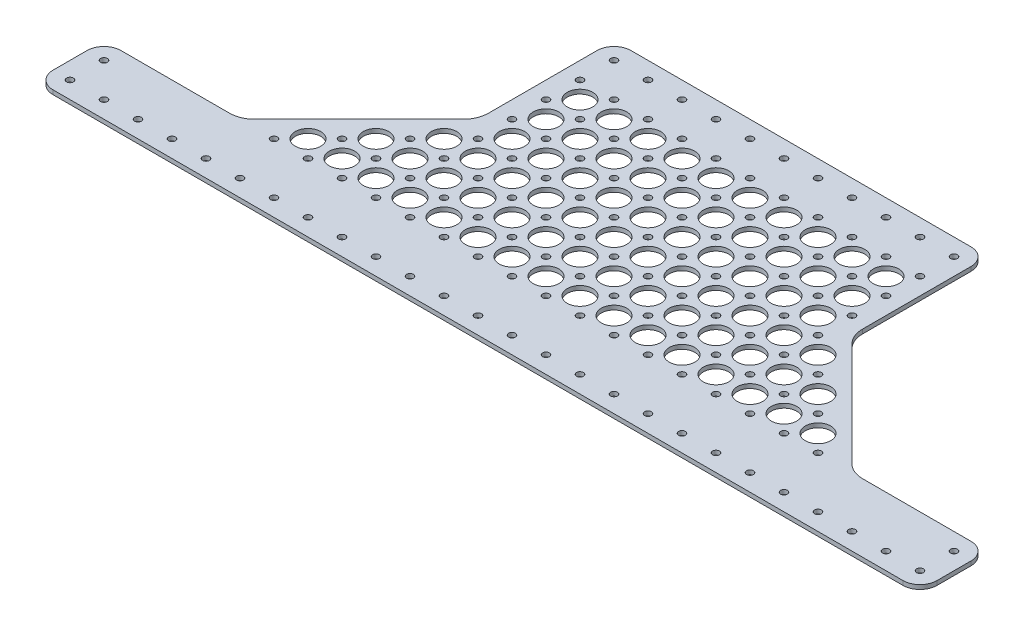
SolidWorks part; units mm, degrees
material "6061 Alloy"
ref_plane "Front Plane" through (0, 0, 0) normal (0, 0, 1) x (1, 0, 0)
ref_plane "Top Plane" through (0, 0, 0) normal (0, 1, 0) x (1, 0, 0)
ref_plane "Right Plane" through (0, 0, 0) normal (1, 0, 0) x (0, 0, -1)
sketch "Sketch1" plane through (0, 0, 0) normal (0, 1, 0) x (1, 0, 0)
  line L0 (0, 0) -> (0, 101.6)
  line L1 (0, 101.6) -> (279.4, 101.6)
  line L2 (279.4, 101.6) -> (279.4, 0)
  line L3 (279.4, 0) -> (368.3045, -88.9045)
  line L4 (368.3045, -88.9045) -> (469.9045, -88.9045)
  line L5 (469.9045, -88.9045) -> (469.9045, -419.1045)
  line L6 (469.9045, -419.1045) -> (368.3045, -419.1045)
  line L7 (368.3045, -419.1045) -> (279.4, -508.0091)
  line L8 (279.4, -508.0091) -> (279.4, -609.6091)
  line L9 (279.4, -609.6091) -> (0, -609.6091)
  line L10 (0, -609.6091) -> (0, -508.0091)
  line L11 (0, -508.0091) -> (-88.9045, -419.1045)
  line L12 (-88.9045, -419.1045) -> (-190.5045, -419.1045)
  line L13 (-190.5045, -419.1045) -> (-190.5045, -88.9045)
  line L14 (-190.5045, -88.9045) -> (-88.9045, -88.9045)
  line L15 (-88.9045, -88.9045) -> (0, 0)
  line L16 (-190.5045, -88.9045) -> (-177.8045, -88.9045)
  line L17 (-177.8045, -88.9045) -> (-177.8045, -419.1045) construction
  line L18 (-177.8045, -419.1045) -> (-190.5045, -419.1045)
  line L19 (-177.8045, -101.6045) -> (-177.8045, -127.0045) construction
  line L20 (139.7, -898.4) -> (139.7, 49101.6) construction
  line L21 (-966.4523, 88.9) -> (49033.5477, 88.9) construction
  line L22 (12.7, 88.9) -> (38.1, 88.9) construction
  line L23 (-1190.5045, -254.0045) -> (48809.4955, -254.0045) construction
  line L24 (-190.5045, -368.3045) -> (-88.9045, -368.3045) construction
  line L25 (-88.9045, -368.3045) -> (-88.9045, -419.1045) construction
  line L26 (-101.6045, -406.4045) -> (-127.0045, -406.4045) construction
  line L27 (-101.6045, -381.0045) -> (-127.0045, -381.0045) construction
  line L28 (-1102.5698, -114.3045) -> (48897.4302, -114.3045) construction
  line L29 (-1089.6596, -165.1045) -> (48910.3404, -165.1045) construction
  line L30 (-177.8045, -127.0045) -> (-152.4045, -127.0045) construction
  circle A0 centre (-177.8045, -101.6045) radius 2.54
  circle A1 centre (-177.8045, -127.0045) radius 2.54
  circle A2 centre (-177.8045, -152.4045) radius 2.54
  circle A3 centre (-177.8045, -177.8045) radius 2.54
  circle A4 centre (-177.8045, -203.2045) radius 2.54
  circle A5 centre (-177.8045, -228.6045) radius 2.54
  circle A6 centre (-177.8045, -254.0045) radius 2.54
  circle A7 centre (-177.8045, -279.4045) radius 2.54
  circle A8 centre (-177.8045, -304.8045) radius 2.54
  circle A9 centre (-177.8045, -330.2045) radius 2.54
  circle A10 centre (-177.8045, -355.6045) radius 2.54
  circle A11 centre (-177.8045, -381.0045) radius 2.54
  circle A12 centre (-177.8045, -406.4045) radius 2.54
  circle A13 centre (457.2045, -406.4045) radius 2.54
  circle A14 centre (457.2045, -381.0045) radius 2.54
  circle A15 centre (457.2045, -355.6045) radius 2.54
  circle A16 centre (457.2045, -330.2045) radius 2.54
  circle A17 centre (457.2045, -304.8045) radius 2.54
  circle A18 centre (457.2045, -279.4045) radius 2.54
  circle A19 centre (457.2045, -254.0045) radius 2.54
  circle A20 centre (457.2045, -228.6045) radius 2.54
  circle A21 centre (457.2045, -152.4045) radius 2.54
  circle A22 centre (457.2045, -177.8045) radius 2.54
  circle A23 centre (457.2045, -203.2045) radius 2.54
  circle A24 centre (457.2045, -127.0045) radius 2.54
  circle A25 centre (457.2045, -101.6045) radius 2.54
  circle A26 centre (12.7, 88.9) radius 2.54
  circle A27 centre (38.1, 88.9) radius 2.54
  circle A28 centre (63.5, 88.9) radius 2.54
  circle A29 centre (88.9, 88.9) radius 2.54
  circle A30 centre (114.3, 88.9) radius 2.54
  circle A31 centre (139.7, 88.9) radius 2.54
  circle A32 centre (165.1, 88.9) radius 2.54
  circle A33 centre (190.5, 88.9) radius 2.54
  circle A34 centre (215.9, 88.9) radius 2.54
  circle A35 centre (241.3, 88.9) radius 2.54
  circle A36 centre (266.7, 88.9) radius 2.54
  circle A37 centre (266.7, -596.9091) radius 2.54
  circle A38 centre (241.3, -596.9091) radius 2.54
  circle A39 centre (215.9, -596.9091) radius 2.54
  circle A40 centre (190.5, -596.9091) radius 2.54
  circle A41 centre (165.1, -596.9091) radius 2.54
  circle A42 centre (139.7, -596.9091) radius 2.54
  circle A43 centre (114.3, -596.9091) radius 2.54
  circle A44 centre (88.9, -596.9091) radius 2.54
  circle A45 centre (63.5, -596.9091) radius 2.54
  circle A46 centre (38.1, -596.9091) radius 2.54
  circle A47 centre (12.7, -596.9091) radius 2.54
  circle A48 centre (-101.6045, -381.0045) radius 2.54
  circle A49 centre (-101.6045, -406.4045) radius 2.54
  circle A50 centre (381.0045, -406.4045) radius 2.54
  circle A51 centre (381.0045, -381.0045) radius 2.54
  circle A52 centre (-127.0045, -406.4045) radius 2.54
  circle A53 centre (-152.4045, -406.4045) radius 2.54
  circle A54 centre (-127.0045, -381.0045) radius 2.54
  circle A55 centre (-152.4045, -381.0045) radius 2.54
  circle A56 centre (431.8045, -381.0045) radius 2.54
  circle A57 centre (406.4045, -381.0045) radius 2.54
  circle A58 centre (431.8045, -406.4045) radius 2.54
  circle A59 centre (406.4045, -406.4045) radius 2.54
  circle A60 centre (-152.4045, -127.0045) radius 2.54
  circle A61 centre (-152.4045, -152.4045) radius 2.54
  circle A62 centre (-127.0045, -127.0045) radius 2.54
  circle A63 centre (-127.0045, -152.4045) radius 2.54
  circle A64 centre (-101.6045, -127.0045) radius 2.54
  circle A65 centre (-101.6045, -152.4045) radius 2.54
  circle A66 centre (-76.2045, -127.0045) radius 2.54
  circle A67 centre (-76.2045, -152.4045) radius 2.54
  circle A68 centre (-50.8045, -127.0045) radius 2.54
  circle A69 centre (-50.8045, -152.4045) radius 2.54
  circle A70 centre (-25.4045, -127.0045) radius 2.54
  circle A71 centre (-25.4045, -152.4045) radius 2.54
  circle A72 centre (-0.0045, -127.0045) radius 2.54
  circle A73 centre (-0.0045, -152.4045) radius 2.54
  circle A74 centre (25.3955, -127.0045) radius 2.54
  circle A75 centre (25.3955, -152.4045) radius 2.54
  circle A76 centre (50.7955, -127.0045) radius 2.54
  circle A77 centre (50.7955, -152.4045) radius 2.54
  circle A78 centre (76.1955, -127.0045) radius 2.54
  circle A79 centre (76.1955, -152.4045) radius 2.54
  circle A80 centre (101.5955, -127.0045) radius 2.54
  circle A81 centre (101.5955, -152.4045) radius 2.54
  circle A82 centre (126.9955, -127.0045) radius 2.54
  circle A83 centre (126.9955, -152.4045) radius 2.54
  circle A84 centre (152.3955, -127.0045) radius 2.54
  circle A85 centre (152.3955, -152.4045) radius 2.54
  circle A86 centre (177.7955, -127.0045) radius 2.54
  circle A87 centre (177.7955, -152.4045) radius 2.54
  circle A88 centre (203.1955, -127.0045) radius 2.54
  circle A89 centre (203.1955, -152.4045) radius 2.54
  circle A90 centre (228.5955, -127.0045) radius 2.54
  circle A91 centre (228.5955, -152.4045) radius 2.54
  circle A92 centre (253.9955, -127.0045) radius 2.54
  circle A93 centre (253.9955, -152.4045) radius 2.54
  circle A94 centre (279.3955, -127.0045) radius 2.54
  circle A95 centre (279.3955, -152.4045) radius 2.54
  circle A96 centre (304.7955, -127.0045) radius 2.54
  circle A97 centre (304.7955, -152.4045) radius 2.54
  circle A98 centre (330.1955, -127.0045) radius 2.54
  circle A99 centre (330.1955, -152.4045) radius 2.54
  circle A100 centre (355.5955, -127.0045) radius 2.54
  circle A101 centre (355.5955, -152.4045) radius 2.54
  circle A102 centre (380.9955, -127.0045) radius 2.54
  circle A103 centre (380.9955, -152.4045) radius 2.54
  circle A104 centre (406.3955, -127.0045) radius 2.54
  circle A105 centre (406.3955, -152.4045) radius 2.54
  circle A106 centre (431.7955, -127.0045) radius 2.54
  circle A107 centre (431.7955, -152.4045) radius 2.54
  point P50 (139.7, 101.6)
  point P105 (-190.5045, -254.0045)
  dimension "D11" = 5.08
  dimension "D16" = 5.08
  dimension "D21" = 5.08
  dimension "D22" = 5.08
  dimension "D1" = 135
  dimension "D2" = 135
  dimension "D3" = 135
  dimension "D4" = 135
  dimension "D5" = 101.6
  dimension "D6" = 279.4
  dimension "D7" = 330.2
  dimension "D8" = 101.6
  dimension "D9" = 125.73
  dimension "D10" = 12.7
  dimension "D12" = 12.7
  dimension "D13" = 25.4
  dimension "D15" = 12.7
  dimension "D17" = 12.7
  dimension "D18" = 25.4
  dimension "D19" = 101.6
  dimension "D20" = 50.8
  dimension "D23" = 12.7
  dimension "D24" = 12.7
  dimension "D25" = 12.7
  dimension "D26" = 12.7
  dimension "D27" = 25.4
  dimension "D28" = 25.4
  dimension "D29" = 25.4
  dimension "D30" = 50.8
  dimension "D31" = 25.4
  dimension "D14" = 13
extrude "Boss-Extrude1" add sketch "Sketch1" along normal blind 3.175 contours L15 L14 L13 L12 L11 L10 L9 L8 L7 L6 L5 L4 L3 L2 L1 L0 A107 A106 A105 A104 A103 A102 A101 A100 A99 A98 A97 A96 A95 A94 A93 A92
sketch "Sketch2" plane through (0, 0, 609.6091) normal (0, 0, 1) x (1, 0, 0)
  line L0 (279.4, 0) -> (0, 0) construction
  line L1 (-203.0133, -12.7) -> (508.1867, -12.7)
  line L2 (-203.0133, -12.7) -> (-203.0133, 12.7)
  line L3 (-203.0133, 12.7) -> (508.1867, 12.7)
  line L4 (508.1867, -12.7) -> (508.1867, 12.7)
  line L5 (-203.0133, -12.7) -> (508.1867, 12.7) construction
  line L6 (-203.0133, 12.7) -> (508.1867, -12.7) construction
  point P0 (152.5867, 0)
  dimension "D1" = 711.2
  dimension "D2" = 25.4
extrude "Cut-Extrude2" cut sketch "Sketch2" against normal blind 469.9
sketch "Sketch3" plane through (0, 3.175, 0) normal (0, 1, 0) x (1, 0, 0)
  line L0 (12.7, 88.9) -> (38.1, 88.9) construction
  line L1 (12.7, 88.9) -> (12.7, 63.5) construction
  line L2 (0, 0) -> (0, 101.6) construction
  line L3 (12.7, -88.9) -> (-12.7, -88.9) construction
  line L4 (12.7, -63.5) -> (-12.7, -63.5) construction
  line L5 (12.7, -38.1) -> (-12.7, -38.1) construction
  line L6 (0, 101.6) -> (279.4, 101.6) construction
  line L7 (266.7, -88.9) -> (292.1, -88.9) construction
  line L8 (266.7, -63.5) -> (292.1, -63.5) construction
  line L9 (266.7, -38.1) -> (292.1, -38.1) construction
  line L10 (25.4, 50.8) -> (50.8, 50.8) construction
  line L11 (25.4, 50.8) -> (25.4, 25.4) construction
  line L12 (279.4, 101.6) -> (279.4, 0) construction
  line L13 (25.4, -25.4) -> (0, -25.4) construction
  circle A0 centre (12.7, 88.9) radius 2.54
  circle A1 centre (38.1, 88.9) radius 2.54
  circle A2 centre (63.5, 88.9) radius 2.54
  circle A3 centre (88.9, 88.9) radius 2.54
  circle A4 centre (114.3, 88.9) radius 2.54
  circle A5 centre (139.7, 88.9) radius 2.54
  circle A6 centre (165.1, 88.9) radius 2.54
  circle A7 centre (190.5, 88.9) radius 2.54
  circle A8 centre (215.9, 88.9) radius 2.54
  circle A9 centre (241.3, 88.9) radius 2.54
  circle A10 centre (266.7, 88.9) radius 2.54
  circle A18 centre (12.7, 63.5) radius 2.54
  circle A19 centre (38.1, 63.5) radius 2.54
  circle A20 centre (63.5, 63.5) radius 2.54
  circle A21 centre (88.9, 63.5) radius 2.54
  circle A22 centre (114.3, 63.5) radius 2.54
  circle A23 centre (139.7, 63.5) radius 2.54
  circle A24 centre (165.1, 63.5) radius 2.54
  circle A25 centre (190.5, 63.5) radius 2.54
  circle A26 centre (215.9, 63.5) radius 2.54
  circle A27 centre (241.3, 63.5) radius 2.54
  circle A28 centre (266.7, 63.5) radius 2.54
  circle A36 centre (12.7, 38.1) radius 2.54
  circle A37 centre (38.1, 38.1) radius 2.54
  circle A38 centre (63.5, 38.1) radius 2.54
  circle A39 centre (88.9, 38.1) radius 2.54
  circle A40 centre (114.3, 38.1) radius 2.54
  circle A41 centre (139.7, 38.1) radius 2.54
  circle A42 centre (165.1, 38.1) radius 2.54
  circle A43 centre (190.5, 38.1) radius 2.54
  circle A44 centre (215.9, 38.1) radius 2.54
  circle A45 centre (241.3, 38.1) radius 2.54
  circle A46 centre (266.7, 38.1) radius 2.54
  circle A54 centre (12.7, 12.7) radius 2.54
  circle A55 centre (38.1, 12.7) radius 2.54
  circle A56 centre (63.5, 12.7) radius 2.54
  circle A57 centre (88.9, 12.7) radius 2.54
  circle A58 centre (114.3, 12.7) radius 2.54
  circle A59 centre (139.7, 12.7) radius 2.54
  circle A60 centre (165.1, 12.7) radius 2.54
  circle A61 centre (190.5, 12.7) radius 2.54
  circle A62 centre (215.9, 12.7) radius 2.54
  circle A63 centre (241.3, 12.7) radius 2.54
  circle A64 centre (266.7, 12.7) radius 2.54
  circle A72 centre (12.7, -12.7) radius 2.54
  circle A73 centre (38.1, -12.7) radius 2.54
  circle A74 centre (63.5, -12.7) radius 2.54
  circle A75 centre (88.9, -12.7) radius 2.54
  circle A76 centre (114.3, -12.7) radius 2.54
  circle A77 centre (139.7, -12.7) radius 2.54
  circle A78 centre (165.1, -12.7) radius 2.54
  circle A79 centre (190.5, -12.7) radius 2.54
  circle A80 centre (215.9, -12.7) radius 2.54
  circle A81 centre (241.3, -12.7) radius 2.54
  circle A82 centre (266.7, -12.7) radius 2.54
  circle A90 centre (12.7, -38.1) radius 2.54
  circle A91 centre (38.1, -38.1) radius 2.54
  circle A92 centre (63.5, -38.1) radius 2.54
  circle A93 centre (88.9, -38.1) radius 2.54
  circle A94 centre (114.3, -38.1) radius 2.54
  circle A95 centre (139.7, -38.1) radius 2.54
  circle A96 centre (165.1, -38.1) radius 2.54
  circle A97 centre (190.5, -38.1) radius 2.54
  circle A98 centre (215.9, -38.1) radius 2.54
  circle A99 centre (241.3, -38.1) radius 2.54
  circle A100 centre (266.7, -38.1) radius 2.54
  circle A108 centre (12.7, -63.5) radius 2.54
  circle A109 centre (38.1, -63.5) radius 2.54
  circle A110 centre (63.5, -63.5) radius 2.54
  circle A111 centre (88.9, -63.5) radius 2.54
  circle A112 centre (114.3, -63.5) radius 2.54
  circle A113 centre (139.7, -63.5) radius 2.54
  circle A114 centre (165.1, -63.5) radius 2.54
  circle A115 centre (190.5, -63.5) radius 2.54
  circle A116 centre (215.9, -63.5) radius 2.54
  circle A117 centre (241.3, -63.5) radius 2.54
  circle A118 centre (266.7, -63.5) radius 2.54
  circle A126 centre (12.7, -88.9) radius 2.54
  circle A127 centre (38.1, -88.9) radius 2.54
  circle A128 centre (63.5, -88.9) radius 2.54
  circle A129 centre (88.9, -88.9) radius 2.54
  circle A130 centre (114.3, -88.9) radius 2.54
  circle A131 centre (139.7, -88.9) radius 2.54
  circle A132 centre (165.1, -88.9) radius 2.54
  circle A133 centre (190.5, -88.9) radius 2.54
  circle A134 centre (215.9, -88.9) radius 2.54
  circle A135 centre (241.3, -88.9) radius 2.54
  circle A136 centre (266.7, -88.9) radius 2.54
  circle A211 centre (-12.7, -88.9) radius 2.54
  circle A212 centre (-38.1, -88.9) radius 2.54
  circle A213 centre (-63.5, -88.9) radius 2.54
  circle A214 centre (-12.7, -63.5) radius 2.54
  circle A215 centre (-38.1, -63.5) radius 2.54
  circle A216 centre (-12.7, -38.1) radius 2.54
  circle A224 centre (292.1, -88.9) radius 2.54
  circle A225 centre (317.5, -88.9) radius 2.54
  circle A226 centre (342.9, -88.9) radius 2.54
  circle A227 centre (292.1, -63.5) radius 2.54
  circle A228 centre (317.5, -63.5) radius 2.54
  circle A229 centre (292.1, -38.1) radius 2.54
  circle A230 centre (25.4, 50.8) radius 9.525
  circle A231 centre (50.8, 50.8) radius 9.525
  circle A232 centre (292.1, 88.9) radius 2.54 [skipped]
  circle A233 centre (317.5, 88.9) radius 2.54 [skipped]
  circle A234 centre (342.9, 88.9) radius 2.54 [skipped]
  circle A235 centre (368.3, 88.9) radius 2.54 [skipped]
  circle A236 centre (393.7, 88.9) radius 2.54 [skipped]
  circle A237 centre (419.1, 88.9) radius 2.54 [skipped]
  circle A238 centre (444.5, 88.9) radius 2.54 [skipped]
  circle A239 centre (12.7, -114.3) radius 2.54 [skipped]
  circle A240 centre (38.1, -114.3) radius 2.54 [skipped]
  circle A241 centre (63.5, -114.3) radius 2.54 [skipped]
  circle A242 centre (88.9, -114.3) radius 2.54 [skipped]
  circle A243 centre (114.3, -114.3) radius 2.54 [skipped]
  circle A244 centre (139.7, -114.3) radius 2.54 [skipped]
  circle A245 centre (165.1, -114.3) radius 2.54 [skipped]
  circle A246 centre (190.5, -114.3) radius 2.54 [skipped]
  circle A247 centre (215.9, -114.3) radius 2.54 [skipped]
  circle A248 centre (241.3, -114.3) radius 2.54 [skipped]
  circle A249 centre (266.7, -114.3) radius 2.54 [skipped]
  circle A250 centre (76.2, 50.8) radius 9.525
  circle A251 centre (101.6, 50.8) radius 9.525
  circle A252 centre (127, 50.8) radius 9.525
  circle A253 centre (152.4, 50.8) radius 9.525
  circle A254 centre (177.8, 50.8) radius 9.525
  circle A255 centre (203.2, 50.8) radius 9.525
  circle A256 centre (228.6, 50.8) radius 9.525
  circle A257 centre (254, 50.8) radius 9.525
  circle A265 centre (50.8, 25.4) radius 9.525
  circle A266 centre (76.2, 25.4) radius 9.525
  circle A267 centre (101.6, 25.4) radius 9.525
  circle A268 centre (127, 25.4) radius 9.525
  circle A269 centre (152.4, 25.4) radius 9.525
  circle A270 centre (177.8, 25.4) radius 9.525
  circle A271 centre (203.2, 25.4) radius 9.525
  circle A272 centre (228.6, 25.4) radius 9.525
  circle A273 centre (254, 25.4) radius 9.525
  circle A281 centre (50.8, 0) radius 9.525
  circle A282 centre (76.2, 0) radius 9.525
  circle A283 centre (101.6, 0) radius 9.525
  circle A284 centre (127, 0) radius 9.525
  circle A285 centre (152.4, 0) radius 9.525
  circle A286 centre (177.8, 0) radius 9.525
  circle A287 centre (203.2, 0) radius 9.525
  circle A288 centre (228.6, 0) radius 9.525
  circle A289 centre (254, 0) radius 9.525
  circle A297 centre (50.8, -25.4) radius 9.525
  circle A298 centre (76.2, -25.4) radius 9.525
  circle A299 centre (101.6, -25.4) radius 9.525
  circle A300 centre (127, -25.4) radius 9.525
  circle A301 centre (152.4, -25.4) radius 9.525
  circle A302 centre (177.8, -25.4) radius 9.525
  circle A303 centre (203.2, -25.4) radius 9.525
  circle A304 centre (228.6, -25.4) radius 9.525
  circle A305 centre (254, -25.4) radius 9.525
  circle A306 centre (279.4, -25.4) radius 9.525
  circle A313 centre (50.8, -50.8) radius 9.525
  circle A314 centre (76.2, -50.8) radius 9.525
  circle A315 centre (101.6, -50.8) radius 9.525
  circle A316 centre (127, -50.8) radius 9.525
  circle A317 centre (152.4, -50.8) radius 9.525
  circle A318 centre (177.8, -50.8) radius 9.525
  circle A319 centre (203.2, -50.8) radius 9.525
  circle A320 centre (228.6, -50.8) radius 9.525
  circle A321 centre (254, -50.8) radius 9.525
  circle A322 centre (279.4, -50.8) radius 9.525
  circle A323 centre (304.8, -50.8) radius 9.525
  circle A329 centre (50.8, -76.2) radius 9.525
  circle A330 centre (76.2, -76.2) radius 9.525
  circle A331 centre (101.6, -76.2) radius 9.525
  circle A332 centre (127, -76.2) radius 9.525
  circle A333 centre (152.4, -76.2) radius 9.525
  circle A334 centre (177.8, -76.2) radius 9.525
  circle A335 centre (203.2, -76.2) radius 9.525
  circle A336 centre (228.6, -76.2) radius 9.525
  circle A337 centre (254, -76.2) radius 9.525
  circle A338 centre (279.4, -76.2) radius 9.525
  circle A339 centre (304.8, -76.2) radius 9.525
  circle A340 centre (330.2, -76.2) radius 9.525
  circle A345 centre (25.4, 25.4) radius 9.525
  circle A346 centre (25.4, 0) radius 9.525
  circle A347 centre (25.4, -25.4) radius 9.525
  circle A348 centre (25.4, -50.8) radius 9.525
  circle A349 centre (25.4, -76.2) radius 9.525
  circle A350 centre (279.4, 25.4) radius 9.525 [skipped]
  circle A351 centre (304.8, 25.4) radius 9.525 [skipped]
  circle A352 centre (330.2, 25.4) radius 9.525 [skipped]
  circle A353 centre (355.6, 25.4) radius 9.525 [skipped]
  circle A354 centre (381, 25.4) radius 9.525 [skipped]
  circle A355 centre (406.4, 25.4) radius 9.525 [skipped]
  circle A356 centre (431.8, 25.4) radius 9.525 [skipped]
  circle A357 centre (279.4, 0) radius 9.525 [skipped]
  circle A358 centre (304.8, 0) radius 9.525 [skipped]
  circle A359 centre (330.2, 0) radius 9.525 [skipped]
  circle A360 centre (355.6, 0) radius 9.525 [skipped]
  circle A361 centre (381, 0) radius 9.525 [skipped]
  circle A362 centre (406.4, 0) radius 9.525 [skipped]
  circle A363 centre (431.8, 0) radius 9.525 [skipped]
  circle A364 centre (304.8, 50.8) radius 9.525 [skipped]
  circle A365 centre (330.2, 50.8) radius 9.525 [skipped]
  circle A366 centre (355.6, 50.8) radius 9.525 [skipped]
  circle A367 centre (381, 50.8) radius 9.525 [skipped]
  circle A368 centre (406.4, 50.8) radius 9.525 [skipped]
  circle A369 centre (431.8, 50.8) radius 9.525 [skipped]
  circle A370 centre (279.4, 50.8) radius 9.525 [skipped]
  circle A371 centre (330.2, -25.4) radius 9.525 [skipped]
  circle A372 centre (355.6, -25.4) radius 9.525 [skipped]
  circle A373 centre (381, -25.4) radius 9.525 [skipped]
  circle A374 centre (406.4, -25.4) radius 9.525 [skipped]
  circle A375 centre (431.8, -25.4) radius 9.525 [skipped]
  circle A376 centre (381, -50.8) radius 9.525 [skipped]
  circle A377 centre (406.4, -50.8) radius 9.525 [skipped]
  circle A378 centre (431.8, -50.8) radius 9.525 [skipped]
  circle A379 centre (406.4, -76.2) radius 9.525 [skipped]
  circle A380 centre (431.8, -76.2) radius 9.525 [skipped]
  circle A381 centre (381, -76.2) radius 9.525 [skipped]
  circle A382 centre (355.6, -76.2) radius 9.525 [skipped]
  circle A383 centre (355.6, -50.8) radius 9.525 [skipped]
  circle A384 centre (330.2, -50.8) radius 9.525 [skipped]
  circle A385 centre (304.8, -25.4) radius 9.525 [skipped]
  circle A386 centre (0, -25.4) radius 9.525
  circle A387 centre (0, -50.8) radius 9.525
  circle A388 centre (0, -76.2) radius 9.525
  circle A390 centre (-25.4, -50.8) radius 9.525
  circle A391 centre (-25.4, -76.2) radius 9.525
  circle A394 centre (-50.8, -76.2) radius 9.525
  circle A395 centre (-50.8, -25.4) radius 9.525 [skipped]
  circle A396 centre (-50.8, -50.8) radius 9.525 [skipped]
  circle A397 centre (-25.4, -25.4) radius 9.525 [skipped]
  dimension "D1" = 5.08
  dimension "D6" = 19.05
  dimension "D2" = 25.4
  dimension "D4" = 25.4
  dimension "D7" = 25.4
  dimension "D8" = 25.4
  dimension "D9" = 25.4
  dimension "D10" = 25.4
  dimension "D11" = 25.4
  dimension "D12" = 25.4
  dimension "D13" = 25.4
  dimension "D14" = 50.8
  dimension "D16" = 25.4
  dimension "D17" = 25.4
  dimension "D19" = 25.4
  dimension "D20" = 25.4
  dimension "D3" = 18
  dimension "D5" = 9
  dimension "D18" = 17
  dimension "D15" = 6
  dimension "D21" = 4
extrude "Cut-Extrude3" cut sketch "Sketch3" against normal blind 3.175
fillet "Fillet1" radius 12.7 6 edges at (-190.5045, 1.5875, 88.9045) (-190.5045, 1.5875, 139.7091) (469.9045, 1.5875, 88.9045) (469.9045, 1.5875, 139.7091) (279.4, 1.5875, -101.6) (0, 1.5875, -101.6)
fillet "Fillet2" radius 19.05 4 edges at (368.3045, 1.5875, 88.9045) (279.4, 1.5875, 0) (-88.9045, 1.5875, 88.9045) (0, 1.5875, 0)
sketch "Sketch4" plane through (0, 0, 0) normal (0, -1, 0) x (1, 0, 0)
  line L0 (-1189.9314, 139.7091) -> (48810.0686, 139.7091) construction
  line L1 (-190.5045, -850.8511) -> (-190.5045, 49149.1489) construction
  line L4 (457.2045, 139.7091) -> (-177.8045, 139.7091) construction
  line L5 (-190.5045, 127.0091) -> (-190.5045, 101.6045) construction
  point P3 (-190.5045, 139.7091)
